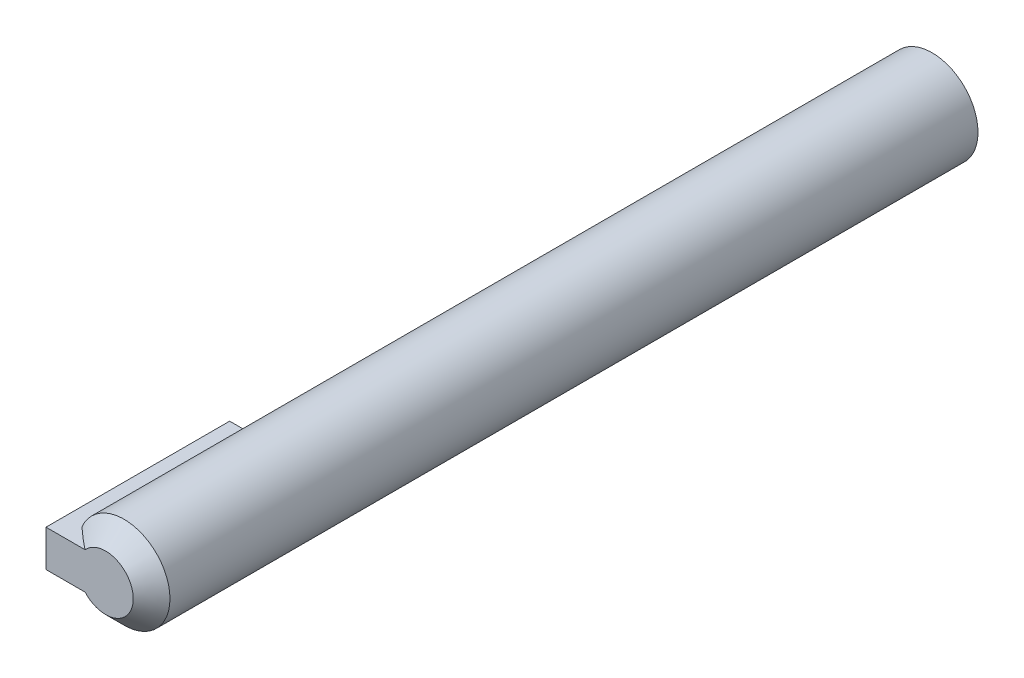
SolidWorks part; units mm, degrees
material "6061 合金"
ref_plane "前视基准面" through (0, 0, 0) normal (0, 0, 1) x (1, 0, 0)
ref_plane "上视基准面" through (0, 0, 0) normal (0, 1, 0) x (1, 0, 0)
ref_plane "右视基准面" through (0, 0, 0) normal (1, 0, 0) x (0, 0, -1)
sketch "草图1" plane through (0, 0, 0) normal (0, 0, 1) x (1, 0, 0)
  circle A0 centre (0, 0) radius 5
  dimension "D1" = 10
extrude "凸台-拉伸1" add sketch "草图1" along normal blind 90
sketch "草图2" plane through (0, 0, 90) normal (0, 0, 1) x (1, 0, 0)
  line L1 (-6.5, 2) -> (0, 2)
  line L2 (-6.5, 2) -> (-6.5, -2)
  line L3 (-6.5, -2) -> (0, -2)
  line L4 (0, 2) -> (0, -2)
  point P4 (0, 0)
  dimension "D1" = 4
  dimension "D2" = 6.5
extrude "凸台-拉伸2" add sketch "草图2" against normal blind 20
chamfer "倒角1" distance 2 angle 45 1 edges at (5, 0, 90)
